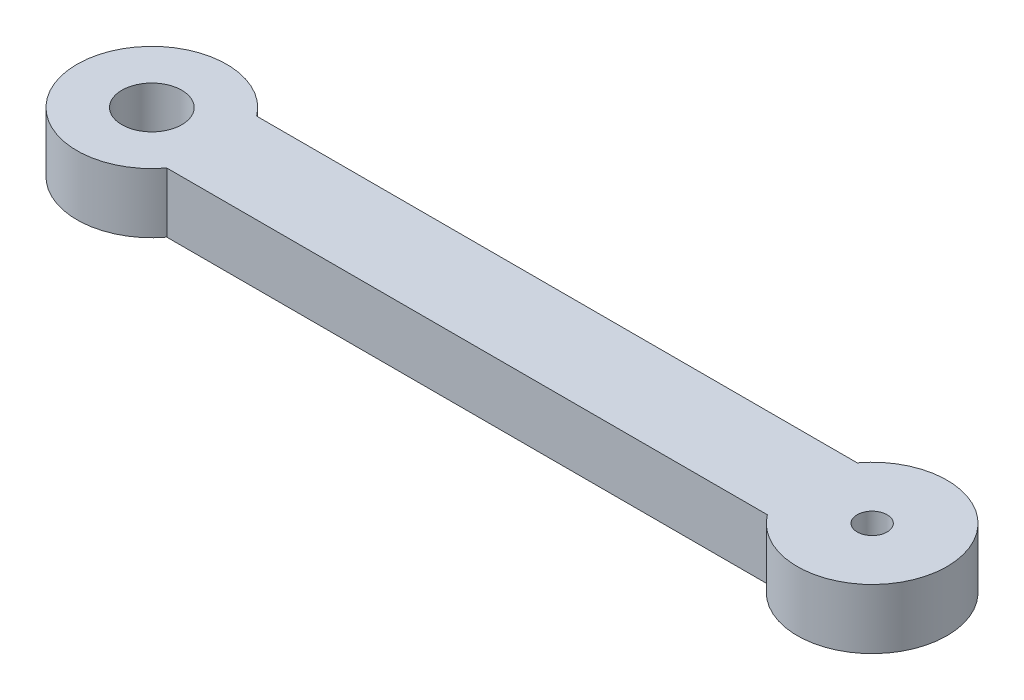
SolidWorks part; units mm, degrees
ref_plane "Front Plane" through (0, 0, 0) normal (0, 0, 1) x (1, 0, 0)
ref_plane "Top Plane" through (0, 0, 0) normal (0, 1, 0) x (1, 0, 0)
ref_plane "Right Plane" through (0, 0, 0) normal (1, 0, 0) x (0, 0, -1)
sketch "Sketch1" plane through (0, 0, 0) normal (0, 1, 0) x (1, 0, 0)
  line L0 (-10.025, 1.5) -> (10.025, 1.5)
  line L1 (-10.025, -1.5) -> (10.025, -1.5)
  line L2 (-12.025, 0) -> (12.025, 0) construction
  arc A0 (10.025, -1.5) -> (10.025, 1.5) centre (12.025, 0) ccw
  arc A1 (-10.025, 1.5) -> (-10.025, -1.5) centre (-12.025, 0) ccw
  circle A2 centre (12.025, 0) radius 0.5
  circle A3 centre (-12.025, 0) radius 1
  dimension "D1" = 5
  dimension "D3" = 2
  dimension "D5" = 1
  dimension "D2" = 24.05
  dimension "D4" = 3
extrude "Boss-Extrude1" add sketch "Sketch1" along normal blind 2
